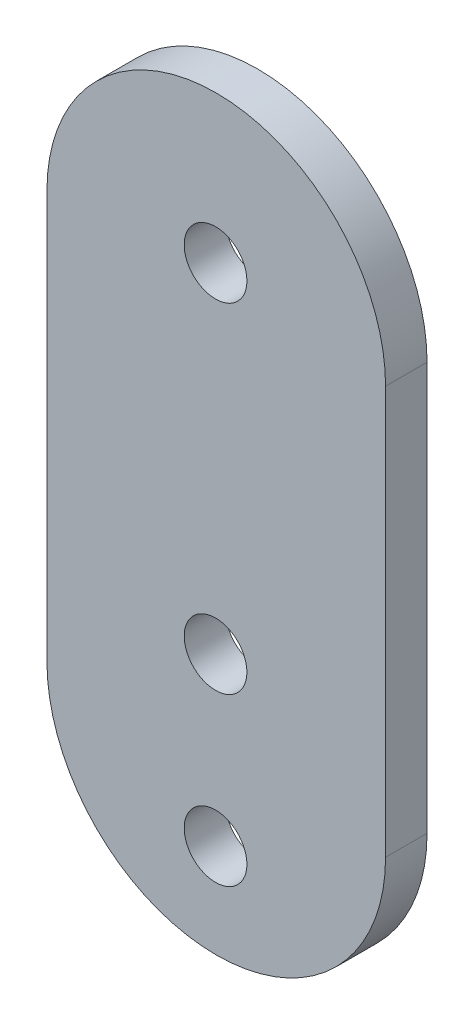
SolidWorks part; units mm, degrees
ref_plane "Front Plane" through (0, 0, 0) normal (0, 0, 1) x (1, 0, 0)
ref_plane "Top Plane" through (0, 0, 0) normal (0, 1, 0) x (1, 0, 0)
ref_plane "Right Plane" through (0, 0, 0) normal (1, 0, 0) x (0, 0, -1)
sketch "Sketch1" plane through (0, 0, 0) normal (0, 0, 1) x (1, 0, 0)
  line L2 (-29.8663, 39.2454) -> (-29.8663, 11.9241)
  line L4 (-7.1877, 39.2454) -> (-7.1877, 11.9241)
  arc A0 (-7.1877, 39.2454) -> (-29.8663, 39.2454) centre (-18.527, 39.2454) ccw
  arc A1 (-29.8663, 11.9241) -> (-7.1877, 11.9241) centre (-18.527, 11.9241) ccw
  point P1 (-18.527, 50.5848)
  point P3 (-18.527, 0.5848)
  dimension "D1" = 50
extrude "Boss-Extrude1" add sketch "Sketch1" along normal blind 2.7781
sketch "Sketch3" plane through (0, 0, 2.7781) normal (0, 0, 1) x (1, 0, 0)
  circle A0 centre (-18.574, 6.8713) radius 2.1
  circle A1 centre (-18.574, 18.0104) radius 2.1
  circle A2 centre (-18.574, 40.7067) radius 2.1
  point P6 (-19.7718, 20.5012)
  point P7 (-19.7718, 7.7181)
  point P8 (-18.574, 25.4849)
  point P9 (-18.574, 18.0104)
  point P10 (-18.574, 6.8713)
extrude "Cut-Extrude1" cut sketch "Sketch3" against normal blind 10
